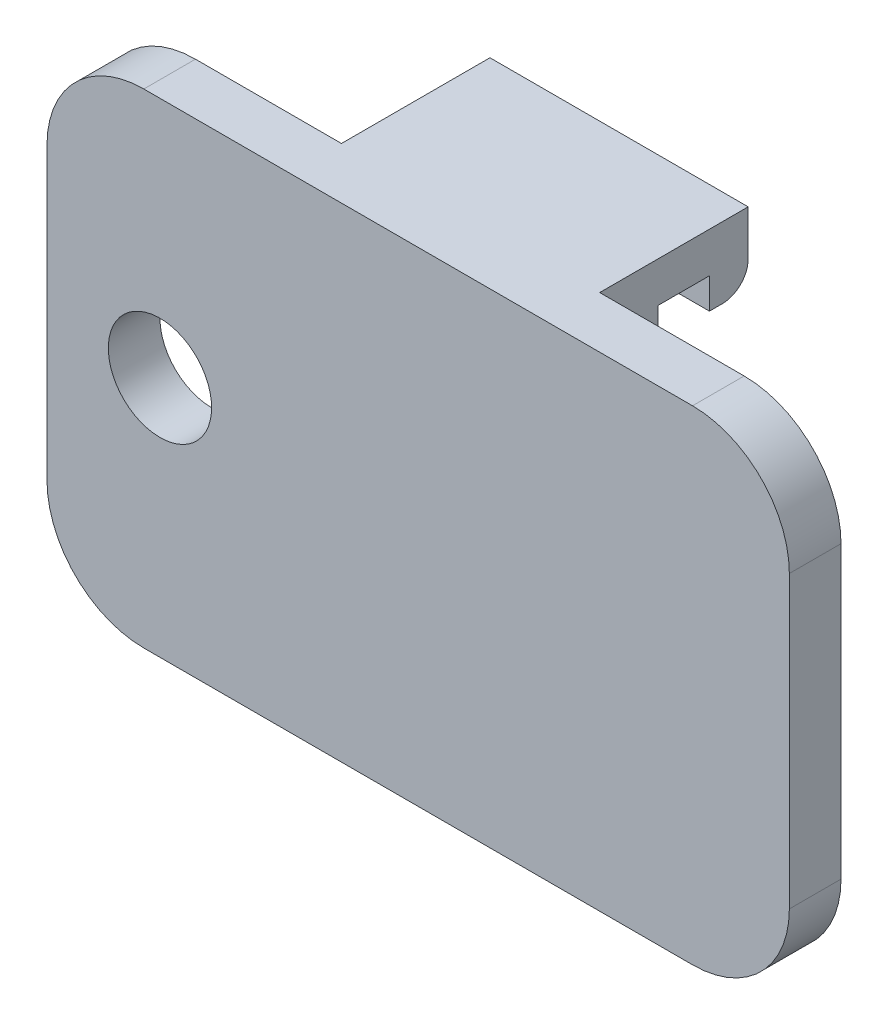
SolidWorks part; units mm, degrees
ref_plane "前视基准面" through (0, 0, 0) normal (0, 0, 1) x (1, 0, 0)
ref_plane "上视基准面" through (0, 0, 0) normal (0, 1, 0) x (1, 0, 0)
ref_plane "右视基准面" through (0, 0, 0) normal (1, 0, 0) x (0, 0, -1)
sketch "草图1" plane through (0, 0, 0) normal (0, 0, 1) x (1, 0, 0)
  line L0 (-4, 6.1941) -> (-4, -6.3509) construction
  line L1 (11.5, -7.5) -> (-11.5, -7.5)
  line L2 (11.5, -7.5) -> (11.5, 7.5)
  line L3 (11.5, 7.5) -> (-11.5, 7.5)
  line L4 (-11.5, -7.5) -> (-11.5, 7.5)
  line L5 (11.5, -7.5) -> (-11.5, 7.5) construction
  line L6 (11.5, 7.5) -> (-11.5, -7.5) construction
  circle A0 centre (-8, 0) radius 1.6
  circle A1 centre (-4, 4.4) radius 1 construction
  circle A2 centre (-4, -4.4) radius 1 construction
  point P0 (0, 0)
  dimension "D3" = 8
  dimension "D5" = 4.4
  dimension "D1" = 23
  dimension "D2" = 15
  dimension "D4" = 4
  dimension "D6" = 4.4
extrude "凸台-拉伸1" add sketch "草图1" along normal blind 1.6
sketch "草图2" plane through (0, 0, 0) normal (0, 0, -1) x (-1, 0, 0)
  line L0 (-11.5, 7.5) -> (11.5, 7.5) construction
  line L5 (3.9764, 7.5) -> (-4.0236, 7.5)
  line L6 (3.9764, 7.5) -> (3.9764, 3.5)
  line L11 (3.9764, 3.5) -> (-4.0236, 3.5)
  line L12 (-4.0236, 7.5) -> (-4.0236, 3.5)
  line L13 (3.9764, 7.5) -> (-4.0236, 3.5) construction
  line L14 (3.9764, 3.5) -> (-4.0236, 7.5) construction
  line L15 (0, 0) -> (-6.9878, 0) construction
  line L16 (-11.5, 7.5) -> (11.5, -7.5) construction
  line L17 (3.9764, -3.5) -> (-4.0236, -3.5)
  line L18 (-4.0236, -7.5) -> (-4.0236, -3.5)
  line L19 (3.9764, -7.5) -> (-4.0236, -7.5)
  line L20 (3.9764, -7.5) -> (3.9764, -3.5)
  point P0 (-0.0236, 5.5)
  point P1 (-0.0236, 5.5)
  point P6 (0.0141, -5)
  dimension "D1" = 4
  dimension "D2" = 8
extrude "凸台-拉伸2" add sketch "草图2" along normal blind 1.8
sketch "草图4" plane through (0, 0, -1.8) normal (0, 0, -1) x (-1, 0, 0)
  line L0 (-4.0236, 7.5) -> (-4.0236, 3.5) construction
  line L1 (-4.0236, 6.25) -> (3.9764, 6.25)
  line L2 (-4.0236, 6.25) -> (-4.0236, 7.5)
  line L3 (-4.0236, 7.5) -> (3.9764, 7.5)
  line L4 (3.9764, 6.25) -> (3.9764, 7.5)
  line L5 (-4.0236, 6.25) -> (3.9764, 7.5) construction
  line L6 (-4.0236, 7.5) -> (3.9764, 6.25) construction
  line L7 (0, 0) -> (5.0212, 0) construction
  line L8 (-4.0236, -7.5) -> (3.9764, -7.5)
  line L9 (3.9764, -6.25) -> (3.9764, -7.5)
  line L10 (-4.0236, -6.25) -> (3.9764, -6.25)
  line L11 (-4.0236, -6.25) -> (-4.0236, -7.5)
  point P0 (-0.0236, 6.875)
  dimension "D1" = 12.5
extrude "凸台-拉伸3" add sketch "草图4" along normal blind 1.6
sketch "草图5" plane through (0, 0, -3.4) normal (0, 0, -1) x (-1, 0, 0)
  line L0 (3.9764, 3.5) -> (3.9764, 7.5) construction
  line L1 (-4.0236, 5.3) -> (3.9764, 5.3)
  line L2 (-4.0236, 5.3) -> (-4.0236, 7.5)
  line L3 (-4.0236, 7.5) -> (3.9764, 7.5)
  line L4 (3.9764, 5.3) -> (3.9764, 7.5)
  line L5 (-4.0236, 5.3) -> (3.9764, 7.5) construction
  line L6 (-4.0236, 7.5) -> (3.9764, 5.3) construction
  line L7 (3.9764, 6.25) -> (3.9764, 7.5) construction
  line L8 (-4.0236, 7.5) -> (-4.0236, 3.5) construction
  line L9 (0, 0) -> (5.3054, 0) construction
  line L10 (-4.0236, -7.5) -> (3.9764, -7.5)
  line L11 (3.9764, -5.3) -> (3.9764, -7.5)
  line L12 (-4.0236, -5.3) -> (3.9764, -5.3)
  line L13 (-4.0236, -5.3) -> (-4.0236, -7.5)
  point P0 (-0.0236, 6.4)
  dimension "D1" = 10.6
extrude "凸台-拉伸4" add sketch "草图5" along normal blind 1.2
fillet "圆角1" radius 0.8 2 edges at (0.0236, -5.3, -4.6) (0.0236, 5.3, -4.6)
fillet "圆角2" radius 3 4 edges at (11.5, -7.5, 0.8) (11.5, 7.5, 0.8) (-11.5, -7.5, 0.8) (-11.5, 7.5, 0.8)
